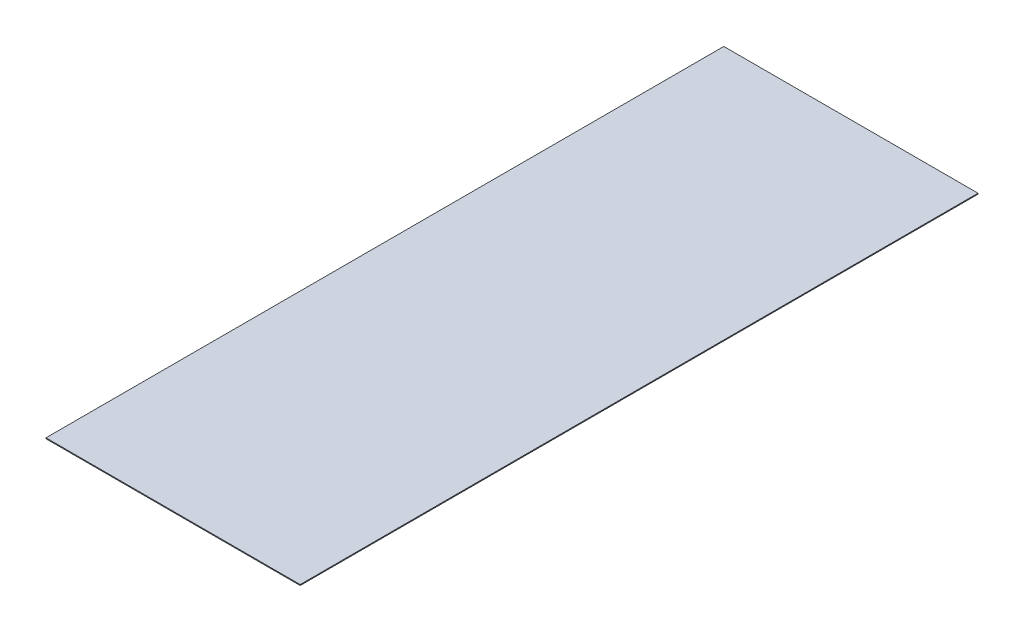
SolidWorks part; units mm, degrees
material "ASTM A36 Acero"
ref_plane "Alzado" through (0, 0, 0) normal (0, 0, 1) x (1, 0, 0)
ref_plane "Planta" through (0, 0, 0) normal (0, 1, 0) x (1, 0, 0)
ref_plane "Vista lateral" through (0, 0, 0) normal (1, 0, 0) x (0, 0, -1)
sketch "Croquis1" plane through (0, 0, 0) normal (0, 1, 0) x (1, 0, 0)
  line L1 (-457.2, -1219.2) -> (457.2, -1219.2)
  line L2 (-457.2, -1219.2) -> (-457.2, 1219.2)
  line L3 (-457.2, 1219.2) -> (457.2, 1219.2)
  line L4 (457.2, -1219.2) -> (457.2, 1219.2)
  line L5 (-457.2, -1219.2) -> (457.2, 1219.2) construction
  line L6 (-457.2, 1219.2) -> (457.2, -1219.2) construction
  point P0 (0, 0)
  dimension "D1" = 2438.4
  dimension "D2" = 914.4
extrude "Saliente-Extruir1" add sketch "Croquis1" along normal blind 3.2
